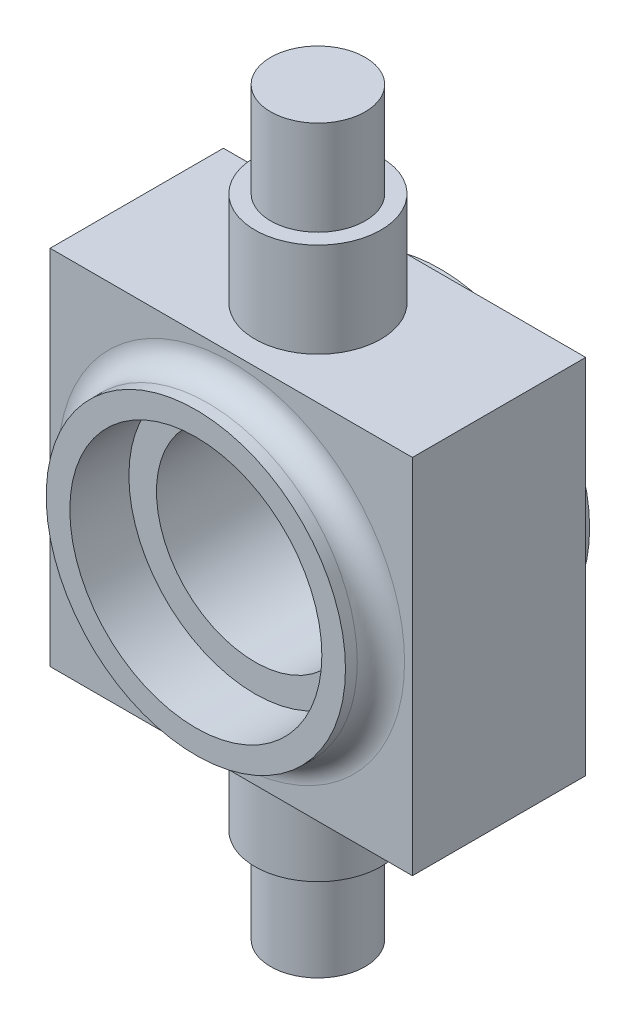
SolidWorks part; units mm, degrees
material "AISI 1020"
ref_plane "Front Plane" through (0, 0, 0) normal (0, 0, 1) x (1, 0, 0)
ref_plane "Top Plane" through (0, 0, 0) normal (0, 1, 0) x (1, 0, 0)
ref_plane "Right Plane" through (0, 0, 0) normal (1, 0, 0) x (0, 0, -1)
sketch "Sketch1" plane through (0, 0, 0) normal (0, 0, 1) x (1, 0, 0)
  line L1 (-23, 23) -> (23, 23)
  line L2 (-23, 23) -> (-23, -23)
  line L3 (-23, -23) -> (23, -23)
  line L4 (23, 23) -> (23, -23)
  line L5 (-23, 23) -> (23, -23) construction
  line L6 (-23, -23) -> (23, 23) construction
  point P0 (0, 0)
  dimension "D1" = 46
  dimension "D2" = 46
extrude "Boss-Extrude1" add sketch "Sketch1" along normal mid plane 22
sketch "Sketch2" plane through (0, 0, 11) normal (0, 0, 1) x (1, 0, 0)
  circle A0 centre (0, 0) radius 16
  dimension "D1" = 32
extrude "Cut-Extrude1" cut sketch "Sketch2" against normal blind 3
sketch "Sketch3" plane through (0, 0, 8) normal (0, 0, 1) x (1, 0, 0)
  circle A0 centre (0, 0) radius 12.5
  dimension "D1" = 25
extrude "Cut-Extrude2" cut sketch "Sketch3" against normal through all
sketch "Sketch4" plane through (0, -23, 0) normal (0, -1, 0) x (1, 0, 0)
  circle A0 centre (0, 0) radius 8
  dimension "D1" = 16
extrude "Boss-Extrude2" add sketch "Sketch4" along normal blind 12
sketch "Sketch5" plane through (0, -35, 0) normal (0, -1, 0) x (1, 0, 0)
  circle A0 centre (0, 0) radius 6
  dimension "D1" = 12
sketch "Sketch6" plane through (0, 0, 11) normal (0, 0, 1) x (1, 0, 0)
  circle A0 centre (0, 0) radius 19
  dimension "D1" = 38
extrude "Boss-Extrude5" add sketch "Sketch6" along normal blind 4.5
sketch "Sketch8" plane through (0, 0, 15.5) normal (0, 0, 1) x (1, 0, 0)
  circle A0 centre (0, 0) radius 16
  dimension "D1" = 32
extrude "Cut-Extrude6" cut sketch "Sketch8" against normal blind 7.5
mirror "Mirror2" about plane through (0, 0, 0) normal (0, 0, 1) of "Boss-Extrude5"
mirror "Mirror3" about plane through (0, 0, 0) normal (0, 0, 1) of "Cut-Extrude6"
fillet "Fillet1" radius 3 2 edges at (19, 0, 11) (19, 0, -11)
sketch "Sketch9" plane through (0, -35, 0) normal (0, -1, 0) x (1, 0, 0)
  circle A0 centre (0, 0) radius 6
  dimension "D1" = 12
extrude "Boss-Extrude6" add sketch "Sketch9" along normal blind 12
cosmetic thread "Cosmetic Thread3" parameters "D1"=8, "D2"=10.072
mirror "Mirror4" about plane through (0, 0, 0) normal (0, 1, 0) of "Boss-Extrude2", "Boss-Extrude6"
cosmetic thread "Cosmetic Thread4" parameters "D1"=8, "D2"=10.072
